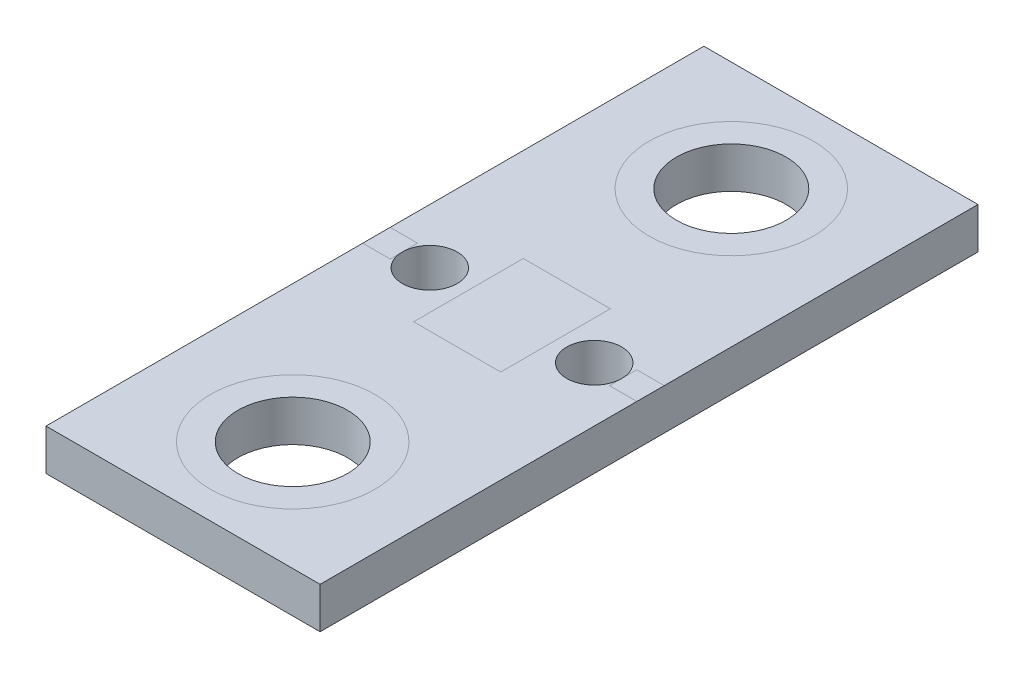
SolidWorks part; units mm, degrees
ref_plane "Front Plane" through (0, 0, 0) normal (0, 0, 1) x (1, 0, 0)
ref_plane "Top Plane" through (0, 0, 0) normal (0, 1, 0) x (1, 0, 0)
ref_plane "Right Plane" through (0, 0, 0) normal (1, 0, 0) x (0, 0, -1)
sketch "Sketch1" plane through (0, 0, 0) normal (0, 1, 0) x (1, 0, 0)
  line L1 (-2.5, 6) -> (2.5, 6)
  line L2 (-2.5, 6) -> (-2.5, -6)
  line L3 (-2.5, -6) -> (2.5, -6)
  line L4 (2.5, 6) -> (2.5, -6)
  line L5 (-2.5, 6) -> (2.5, -6) construction
  line L6 (-2.5, -6) -> (2.5, 6) construction
  circle A0 centre (-1.5, 0) radius 0.5
  circle A1 centre (1.5, 0) radius 0.5
  circle A2 centre (0, -4) radius 1
  circle A3 centre (0, 4) radius 1
  point P0 (0, 0)
  dimension "D3" = 1
  dimension "D7" = 4
  dimension "D8" = 4
  dimension "D1" = 5
  dimension "D2" = 12
  dimension "D4" = 1
  dimension "D5" = 6
  dimension "D6" = 6
extrude "Boss-Extrude1" add sketch "Sketch1" along normal blind 0.75
sketch "Sketch2" plane through (0, 0.75, 0) normal (0, 1, 0) x (1, 0, 0)
  line L1 (-0.7938, 1) -> (0.7937, 1)
  line L2 (-0.7938, 1) -> (-0.7937, -1)
  line L3 (-0.7937, -1) -> (0.7937, -1)
  line L4 (0.7937, 1) -> (0.7937, -1)
  line L5 (-0.7938, 1) -> (0.7937, -1) construction
  line L6 (-0.7937, -1) -> (0.7937, 1) construction
  point P0 (0, 0)
  dimension "D1" = 1.5875
  dimension "D2" = 2
sketch "Sketch3" plane through (0, 0.75, 0) normal (0, 1, 0) x (1, 0, 0)
  line L0 (-2.5, 6) -> (-2.5, -6) construction
  line L1 (-2.5, 0.2775) -> (-2, 0.2775)
  line L2 (-2.5, 0.2775) -> (-2.5, -0.2225)
  line L3 (-2.5, -0.2225) -> (-2, -0.2225)
  line L4 (-2, 0.2775) -> (-2, -0.2225)
  line L5 (-2.5, 0.2775) -> (-2, -0.2225) construction
  line L6 (-2.5, -0.2225) -> (-2, 0.2775) construction
  line L7 (2, 0.2775) -> (2.5, 0.2775)
  line L8 (2, 0.2775) -> (2, -0.2225)
  line L9 (2, -0.2225) -> (2.5, -0.2225)
  line L10 (2.5, 0.2775) -> (2.5, -0.2225)
  line L11 (2, 0.2775) -> (2.5, -0.2225) construction
  line L12 (2, -0.2225) -> (2.5, 0.2775) construction
  line L13 (2.5, -6) -> (2.5, 6) construction
  point P0 (-2.25, 0.0275)
  point P5 (2.25, 0.0275)
  dimension "D1" = 0.5
  dimension "D2" = 0.5
  dimension "D3" = 0.5
  dimension "D4" = 0.5
  dimension "D5" = 0.5
  dimension "D6" = 0.5
split line "Split Line1"
split line "Split Line3"
sketch "Sketch4" plane through (0, 0.75, 0) normal (0, 1, 0) x (1, 0, 0)
  circle A0 centre (0, -4) radius 1.5
  circle A1 centre (0, 4) radius 1.5
split line "Split Line4"
